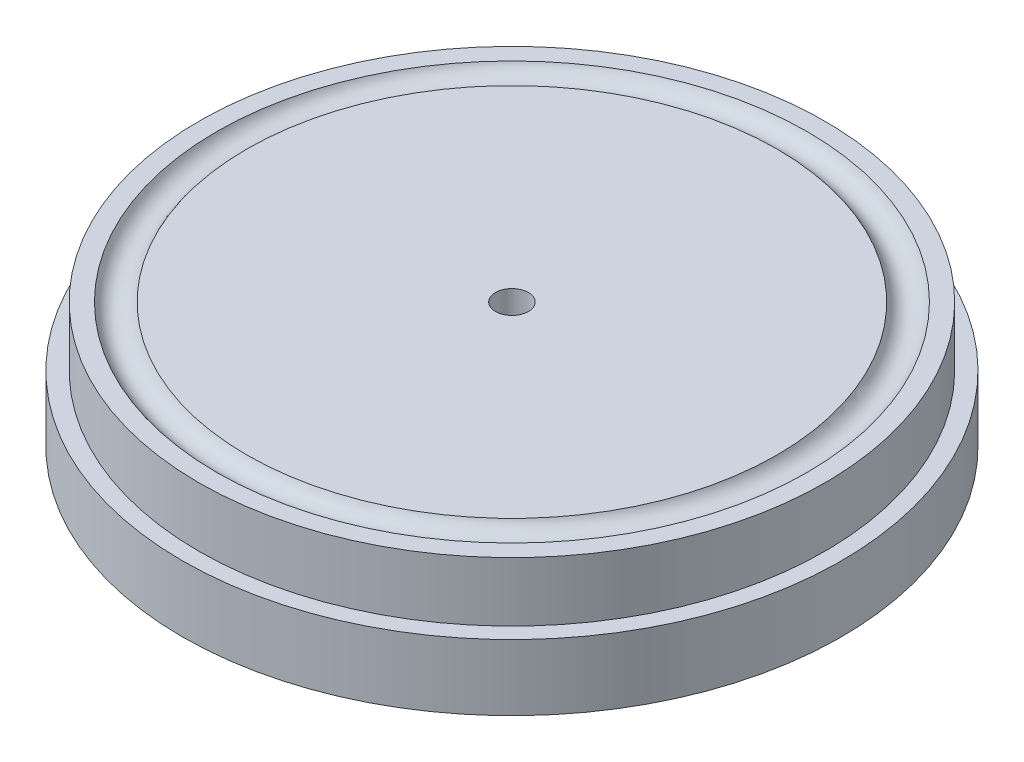
SolidWorks part; units mm, degrees
ref_plane "Front Plane" through (0, 0, 0) normal (0, 0, 1) x (1, 0, 0)
ref_plane "Top Plane" through (0, 0, 0) normal (0, 1, 0) x (1, 0, 0)
ref_plane "Right Plane" through (0, 0, 0) normal (1, 0, 0) x (0, 0, -1)
sketch "Sketch1" plane through (0, 0, 0) normal (0, 1, 0) x (1, 0, 0)
  circle A0 centre (0, 0) radius 50
  dimension "Outer Diameter" = 100
extrude "Boss-Extrude1" add sketch "Sketch1" along normal blind 10
sketch "Sketch3" plane through (0, 10, 0) normal (0, 1, 0) x (1, 0, 0)
  circle A0 centre (0, 0) radius 47.5
  dimension "Lip outer diameter" = 95
extrude "Boss-Extrude2" add sketch "Sketch3" along normal blind 10
sketch "Sketch4" plane through (0, 20, 0) normal (0, 1, 0) x (1, 0, 0)
  circle A2 centre (0, 0) radius 42.5
  circle A3 centre (0, 0) radius 42.5
  dimension "Bearing Path" = 5
sketch "Sketch5" plane through (0, 0, 0) normal (0, 0, 1) x (1, 0, 0)
  line L0 (0, 0) -> (0, 20) construction
  line L1 (42.5, 20) -> (-42.5, 20) construction
  line L2 (0, 20) -> (42.5, 20) construction
  line L3 (47.5, 20) -> (-47.5, 20) construction
  circle A0 centre (42.5, 20) radius 2.5
  dimension "D2" = 5
  dimension "D1" = 42.5
sweep "Cut-Sweep1" cut profiles "Sketch5" path "Sketch4"
sketch "Sketch6" plane through (0, 20, 0) normal (0, 1, 0) x (1, 0, 0)
  line L0 (0, -55.8694) -> (0, 58.2655) construction
  line L1 (60.5463, 0) -> (-59.0949, 0) construction
  circle A0 centre (0, 0) radius 2.5
  dimension "Heated Screw Insert Outer Diameter" = 5
extrude "Cut-Extrude1" cut sketch "Sketch6" against normal blind 5
sketch "Sketch7" plane through (0, 20, 0) normal (0, 1, 0) x (1, 0, 0)
  circle A0 centre (0, 0) radius 47.5 construction
  circle A1 centre (0, 0) radius 47.5
extrude "Cut-Extrude2" cut sketch "Sketch7" against normal blind 1
